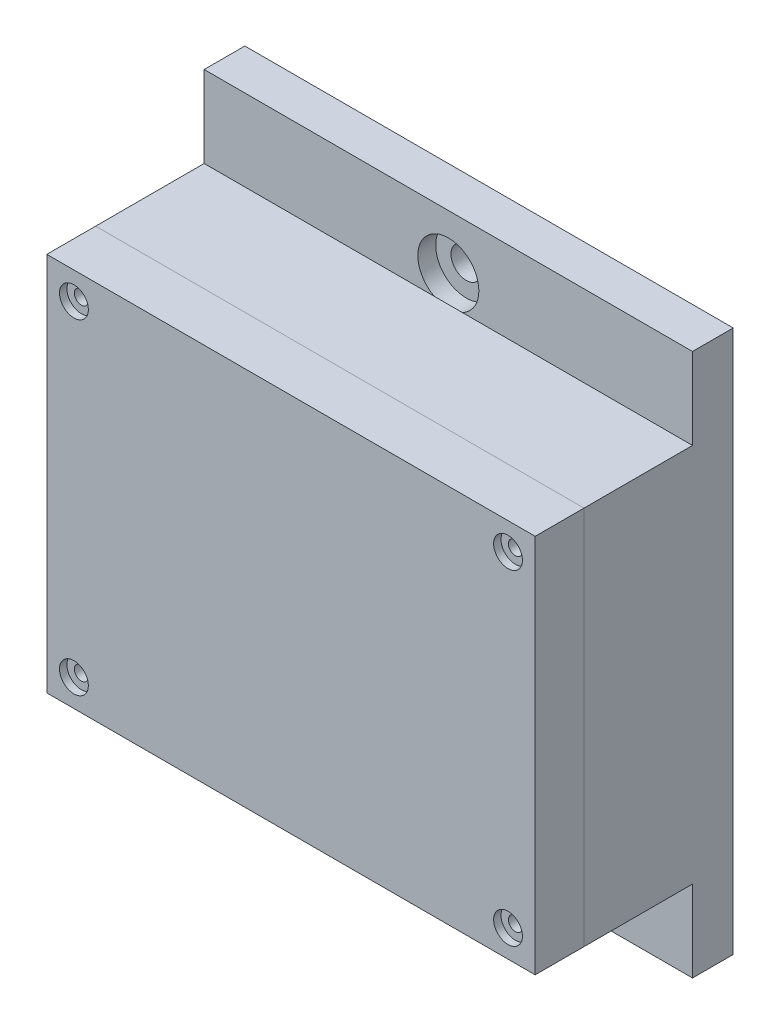
SolidWorks part; units mm, degrees
ref_plane "Front Plane" through (0, 0, 0) normal (0, 0, 1) x (1, 0, 0)
ref_plane "Top Plane" through (0, 0, 0) normal (0, 1, 0) x (1, 0, 0)
ref_plane "Right Plane" through (0, 0, 0) normal (1, 0, 0) x (0, 0, -1)
sketch "Sketch1" plane through (0, 0, 0) normal (0, 0, 1) x (1, 0, 0)
  line L1 (-57.15, 63.5) -> (57.15, 63.5)
  line L2 (-57.15, 63.5) -> (-57.15, -63.5)
  line L3 (-57.15, -63.5) -> (57.15, -63.5)
  line L4 (57.15, 63.5) -> (57.15, -63.5)
  line L5 (-57.15, 63.5) -> (57.15, -63.5) construction
  line L6 (-57.15, -63.5) -> (57.15, 63.5) construction
  point P0 (0, 0)
  dimension "D1" = 127
  dimension "D2" = 114.3
extrude "base" add sketch "Sketch1" along normal blind 9.525
hole_wizard "CBORE for 1/4 Binding Head Machine Screw1" positions "Sketch2" profile "Sketch3" counterbore size "1/4" standard "ANSI Inch" end condition up to next
sketch "Sketch2" plane through (0, 0, 9.525) normal (0, 0, 1) x (1, 0, 0)
  line L12 (-57.15, 63.5) -> (-57.15, -63.5) construction
  line L22 (57.15, -63.5) -> (57.15, 63.5)
  line L23 (57.15, 63.5) -> (-57.15, 63.5)
  line L24 (-57.15, 63.5) -> (-57.15, -63.5)
  line L25 (-57.15, -63.5) -> (57.15, -63.5)
  line L26 (57.15, -63.5) -> (57.15, 63.5)
  line L28 (-57.15, 0) -> (-57.15, -63.5)
  line L29 (-57.15, -63.5) -> (57.15, -63.5)
  line L38 (57.15, 63.5) -> (-57.15, 63.5) construction
  point P2 (0, 50.8)
  point P16 (0, -50.8)
  point P95 (0, 0)
  point P96 (0, 0)
  point P103 (-57.15, -53.0791)
  point P104 (0, 0)
  dimension "D1" = 57.15
  dimension "D2" = 12.7
  dimension "D3" = 12.7
  dimension "D4" = 0
  dimension "D5" = 57.15
sketch "Sketch3" plane through (0, 50.8, 9.525) normal (1, 0, 0) x (0, -1, 0)
  line L0 (0, 0) -> (0, 9.525)
  line L1 (0, 9.525) -> (3.5712, 9.525)
  line L3 (3.5712, 9.525) -> (3.5712, 4.191)
  line L4 (3.5712, 4.191) -> (7.1437, 4.191)
  line L5 (7.1437, 4.191) -> (7.1437, 0)
  line L7 (7.1437, 0) -> (0, 0)
  line L11 (0, -6.35) -> (0, 107.95) construction
  dimension "Thru Hole Dia." = 7.1425
  dimension "Thru Hole Depth" = 9.525
  dimension "C'Bore Dia." = 14.2875
  dimension "C'Bore Depth" = 4.191
sketch "Sketch4" plane through (0, 0, 9.525) normal (0, 0, 1) x (1, 0, 0)
  line L0 (-43.4602, 0) -> (43.4602, 0) construction
  line L1 (-57.15, 44.45) -> (57.15, 44.45)
  line L2 (-57.15, 44.45) -> (-57.15, -44.45)
  line L3 (-57.15, -44.45) -> (57.15, -44.45)
  line L4 (57.15, 44.45) -> (57.15, -44.45)
  line L5 (57.15, 0) -> (43.4602, 0) construction
  line L6 (-43.4602, 0) -> (-57.15, 0) construction
  line L7 (-43.4602, 38.1) -> (43.4602, 38.1)
  line L8 (-43.4602, 38.1) -> (-43.4602, -38.1)
  line L9 (-43.4602, -38.1) -> (43.4602, -38.1)
  line L10 (43.4602, 38.1) -> (43.4602, 18.034)
  line L11 (-43.4602, 38.1) -> (43.4602, -38.1) construction
  line L12 (-43.4602, -38.1) -> (43.4602, 38.1) construction
  line L13 (57.15, 44.45) -> (-57.15, -44.45) construction
  line L14 (3.1115, 38.1) -> (3.1115, 44.45) construction
  line L15 (-35.8402, 30.48) -> (7.3398, 30.48) construction
  line L16 (-35.8402, 30.48) -> (-35.8402, -30.48) construction
  line L17 (-35.8402, -30.48) -> (7.3398, -30.48) construction
  line L18 (7.3398, 30.48) -> (7.3398, -30.48) construction
  line L19 (-35.8402, 30.48) -> (7.3398, -30.48) construction
  line L20 (-35.8402, -30.48) -> (7.3398, 30.48) construction
  line L21 (0, -44.45) -> (0, -38.1) construction
  line L22 (43.4602, -18.034) -> (43.4602, -12.954)
  line L23 (43.4602, 12.954) -> (43.4602, 18.034)
  line L24 (-57.15, 44.45) -> (57.15, -44.45) construction
  line L29 (-57.15, -63.5) -> (57.15, -63.5) construction
  line L30 (-57.15, 63.5) -> (-57.15, -63.5) construction
  line L31 (43.4602, 12.954) -> (43.4602, -12.954)
  line L35 (43.4602, -18.034) -> (43.4602, -38.1)
  line L36 (57.15, 63.5) -> (-57.15, 63.5) construction
  line L37 (43.4602, 0) -> (57.15, 0) construction
  line L38 (57.15, -63.5) -> (57.15, 63.5) construction
  point P5 (-2.4997, -2.1914)
  point P20 (0, 0)
  dimension "D2" = 7.62
  dimension "D3" = 0
  dimension "D4" = 60.96
  dimension "D5" = 43.18
  dimension "D6" = 0
  dimension "D7" = 7.62
  dimension "D8" = 6.35
  dimension "D9" = 13.6898
  dimension "D10" = 21.3098
  dimension "D11" = 33.02
  dimension "D12" = 64.4898
  dimension "D13" = 19.05
  dimension "D14" = 88.9
extrude "Boss-Extrude2" add sketch "Sketch4" along normal blind 25.4
sketch "Sketch11" plane through (0, -44.45, 0) normal (0, -1, 0) x (1, 0, 0)
  line L0 (-37.1102, 34.925) -> (-37.1102, 17.145)
  line L1 (-57.15, 34.925) -> (57.15, 34.925) construction
  line L2 (-37.1102, 17.145) -> (38.3802, 17.145)
  line L3 (38.3802, 17.145) -> (38.3802, 34.925)
  line L4 (38.3802, 34.925) -> (-37.1102, 34.925)
  line L5 (-43.4602, 34.925) -> (-43.4602, 9.525) construction
  dimension "D1" = 17.78
  dimension "D2" = 5.08
  dimension "D3" = 6.35
extrude "Cut-Extrude1" cut sketch "Sketch11" against normal up to next
sketch "Sketch12" plane through (-57.15, 0, 0) normal (-1, 0, 0) x (0, 0, 1)
  line L0 (34.925, 44.45) -> (34.925, -44.45) construction
  line L1 (34.925, 31.75) -> (17.145, 31.75)
  line L2 (34.925, 31.75) -> (34.925, -31.75)
  line L3 (34.925, -31.75) -> (17.145, -31.75)
  line L4 (17.145, 31.75) -> (17.145, -31.75)
  line L5 (34.925, 31.75) -> (17.145, -31.75) construction
  line L6 (34.925, -31.75) -> (17.145, 31.75) construction
  point P0 (26.035, 0)
  dimension "D1" = 6.35
  dimension "D2" = 6.35
  dimension "D3" = 17.78
extrude "Cut-Extrude2" cut sketch "Sketch12" against normal up to next
hole_wizard "#4 Clearance Hole1" positions "Sketch17" profile "Sketch18" hole size "#4" standard "ANSI Inch"
sketch "Sketch17" plane through (0, 0, 34.925) normal (0, 0, 1) x (1, 0, 0)
  line L0 (57.15, -44.45) -> (57.15, 44.45) construction
  line L1 (57.15, 44.45) -> (-57.15, 44.45) construction
  line L3 (38.3802, -44.45) -> (57.15, -44.45) construction
  line L5 (50.8, 38.1) -> (57.15, 38.1) construction
  line L10 (50.8, 38.1) -> (50.8, 44.45) construction
  line L13 (50.8, -38.1) -> (50.8, -44.45) construction
  line L16 (50.8, -38.1) -> (57.15, -38.1) construction
  line L18 (-50.8, 38.1) -> (-57.15, 38.1) construction
  line L19 (-57.15, 44.45) -> (-57.15, 31.75) construction
  line L21 (-50.8, 38.1) -> (-50.8, 44.45) construction
  line L23 (-50.8, -38.1) -> (-50.8, -44.45) construction
  line L24 (-57.15, -44.45) -> (-37.1102, -44.45) construction
  line L26 (-50.8, -38.1) -> (-57.15, -38.1) construction
  line L27 (-57.15, -31.75) -> (-57.15, -44.45) construction
  point P0 (50.8, 38.1)
  point P2 (50.8, -38.1)
  point P4 (-50.8, -38.1)
  point P6 (-50.8, 38.1)
  dimension "D1" = 6.35
sketch "Sketch18" plane through (50.8, 38.1, 34.925) normal (1, 0, 0) x (0, -1, 0)
  line L0 (0, 0) -> (0, 7.3306)
  line L1 (0, 7.3306) -> (1.6319, 6.35)
  line L2 (1.6319, 6.35) -> (1.6319, 0)
  line L5 (1.6319, 0) -> (0, 0)
  line L10 (0, 7.3306) -> (-1.6319, 6.35) construction
  line L11 (0, -6.35) -> (0, 107.95) construction
  dimension "Hole Dia." = 3.2639
  dimension "Hole Depth" = 6.35
  dimension "Drill Angle" = 118
hole_wizard "#4 Clearance Hole2" positions "Sketch21" profile "Sketch20" hole size "#4" standard "ANSI Inch"
sketch "Sketch21" plane through (0, 0, 9.525) normal (0, 0, 1) x (1, 0, 0)
  line L0 (0, 0) -> (-56.3849, 0) construction
  line L2 (-57.15, 31.75) -> (-57.15, -31.75) construction
  line L3 (-57.15, -63.5) -> (57.15, -63.5) construction
  point P0 (-35.814, -30.48)
  point P8 (-35.814, 30.48)
  point P13 (7.366, -30.48)
  point P16 (7.366, 30.48)
  dimension "D1" = 21.336
  dimension "D2" = 33.02
  dimension "D3" = 64.516
sketch "Sketch20" plane through (-35.814, -30.48, 9.525) normal (1, 0, 0) x (0, -1, 0)
  line L0 (0, 0) -> (0, 7.3306)
  line L1 (0, 7.3306) -> (1.6319, 6.35)
  line L2 (1.6319, 6.35) -> (1.6319, 0)
  line L5 (1.6319, 0) -> (0, 0)
  line L10 (0, 7.3306) -> (-1.632, 6.35) construction
  line L11 (0, -6.35) -> (0, 107.95) construction
  dimension "Hole Dia." = 3.2639
  dimension "Hole Depth" = 6.35
  dimension "Drill Angle" = 118
sketch "Sketch23" plane through (0, 0, 9.525) normal (0, 0, 1) x (1, 0, 0)
  line L0 (7.366, 30.48) -> (7.366, -38.1) construction
  line L1 (14.0368, 17.78) -> (20.3868, 17.78)
  line L2 (14.0368, 17.78) -> (14.0368, 5.08)
  line L3 (14.0368, 5.08) -> (20.3868, 5.08)
  line L4 (20.3868, 17.78) -> (20.3868, 5.08)
  line L5 (-43.4602, -38.1) -> (43.4602, -38.1) construction
  line L6 (20.3868, 17.78) -> (14.0368, 5.08) construction
  line L7 (20.3868, 5.08) -> (14.0368, 17.78) construction
  line L8 (-37.1102, -38.1) -> (38.3802, -38.1) construction
  line L9 (28.7485, -38.1) -> (28.7485, 36.8) construction
  line L10 (37.1102, 17.78) -> (43.4602, 5.08) construction
  line L11 (43.4602, 17.78) -> (37.1102, 17.78)
  line L12 (37.1102, 17.78) -> (37.1102, 5.08)
  line L13 (37.1102, 5.08) -> (43.4602, 17.78) construction
  line L14 (43.4602, 5.08) -> (37.1102, 5.08)
  line L15 (43.4602, 17.78) -> (43.4602, 5.08)
  line L16 (43.4602, -38.1) -> (43.4602, 38.1) construction
  point P13 (17.2118, 11.43)
  dimension "D1" = 12.7
  dimension "D2" = 6.35
  dimension "D3" = 0
  dimension "D4" = 43.18
  dimension "D5" = 11.5367
extrude "Boss-Extrude5" add sketch "Sketch23" along normal blind 17.78
hole_wizard "#4 Clearance Hole3" positions "Sketch24" profile "Sketch26" hole size "#4" standard "ANSI Inch"
sketch "Sketch24" plane through (0, 5.08, 0) normal (0, -1, 0) x (-1, 0, 0)
  line L0 (-14.0368, -27.305) -> (-20.3868, -27.305) construction
  line L1 (-37.1102, -27.305) -> (-43.4602, -27.305) construction
  line L2 (-14.0368, -27.305) -> (-14.0368, -9.525) construction
  line L3 (-43.4602, -27.305) -> (-43.4602, -9.525) construction
  point P0 (-17.2118, -20.955)
  point P2 (-40.2852, -20.955)
  dimension "D1" = 6.35
  dimension "D2" = 6.35
  dimension "D3" = 3.175
  dimension "D4" = 3.175
sketch "Sketch26" plane through (17.2118, 5.08, 20.955) normal (1, 0, 0) x (0, 0, -1)
  line L0 (0, 0) -> (0, 7.3306)
  line L1 (0, 7.3306) -> (1.6319, 6.35)
  line L2 (1.6319, 6.35) -> (1.6319, 0)
  line L5 (1.6319, 0) -> (0, 0)
  line L10 (0, 7.3306) -> (-1.632, 6.35) construction
  line L11 (0, -6.35) -> (0, 107.95) construction
  dimension "Hole Dia." = 3.2639
  dimension "Hole Depth" = 6.35
  dimension "Drill Angle" = 118
sketch "Sketch27" plane through (0, 0, 9.525) normal (0, 0, 1) x (1, 0, 0)
  line L0 (-43.4602, -38.1) -> (43.4602, -38.1) construction
  line L1 (14.0368, 5.08) -> (43.4602, 5.08)
  line L2 (14.0368, 5.08) -> (14.0368, -38.1)
  line L3 (14.0368, -38.1) -> (43.4602, -38.1)
  line L4 (43.4602, 5.08) -> (43.4602, -38.1)
  dimension "D1" = 0
  dimension "D2" = 0
extrude "Boss-Extrude6" add sketch "Sketch27" along normal blind 5.08
ref_plane "Plane1" through (0, 0, 40.005) normal (0, 0, 1) x (1, 0, 0)
sketch "Sketch13" plane through (0, 0, 40.005) normal (0, 0, 1) x (1, 0, 0)
  line L0 (-43.4602, 31.75) -> (-57.15, 31.75)
  line L1 (-57.15, 31.75) -> (-57.15, 44.45)
  line L2 (-57.15, 44.45) -> (57.15, 44.45)
  line L3 (57.15, 44.45) -> (57.15, -44.45)
  line L4 (57.15, -44.45) -> (38.3802, -44.45)
  line L5 (38.3802, -44.45) -> (38.3802, -38.1)
  line L6 (38.3802, -38.1) -> (43.4602, -38.1)
  line L7 (43.4602, -38.1) -> (43.4602, 38.1)
  line L8 (43.4602, 38.1) -> (-43.4602, 38.1)
  line L9 (-43.4602, 38.1) -> (-43.4602, 31.75)
  line L10 (-43.4602, -31.75) -> (-57.15, -31.75)
  line L11 (-57.15, -31.75) -> (-57.15, -44.45)
  line L12 (-57.15, -44.45) -> (-37.1102, -44.45)
  line L13 (-37.1102, -44.45) -> (-37.1102, -38.1)
  line L14 (-37.1102, -38.1) -> (-43.4602, -38.1)
  line L15 (-43.4602, -38.1) -> (-43.4602, -31.75)
  line L16 (-57.15, -44.45) -> (-37.1102, -44.45) construction
  line L17 (-37.1102, -38.1) -> (-37.1102, -44.45) construction
  line L18 (-43.4602, -38.1) -> (-37.1102, -38.1) construction
  line L19 (-43.4602, -31.75) -> (-43.4602, -38.1) construction
  line L20 (-43.4602, -31.75) -> (-57.15, -31.75) construction
  line L21 (-57.15, -31.75) -> (-57.15, -44.45) construction
  line L22 (-43.4602, 31.75) -> (-57.15, 31.75) construction
  line L23 (-43.4602, 38.1) -> (-43.4602, 31.75) construction
  line L24 (-57.15, 44.45) -> (-57.15, 31.75) construction
  line L25 (57.15, 44.45) -> (-57.15, 44.45) construction
  line L26 (43.4602, 38.1) -> (-43.4602, 38.1) construction
  line L27 (43.4602, -38.1) -> (43.4602, 38.1) construction
  line L29 (38.3802, -38.1) -> (43.4602, -38.1) construction
  line L30 (38.3802, -44.45) -> (57.15, -44.45) construction
  line L31 (38.3802, -38.1) -> (38.3802, -44.45) construction
  line L32 (57.15, -44.45) -> (57.15, 44.45) construction
extrude "Boss-Extrude3" add sketch "Sketch13" against normal up to surface (5.08 mm away) separate body up to face at (52.4319, 38.1, 34.925)
fillet "Fillet3" radius 2.54 8 edges at (-43.4602, -38.1, 22.225) (43.4602, -38.1, 24.765) (43.4602, 38.1, 22.225) (-43.4602, 38.1, 22.225) (-57.15, 31.75, 26.035) (-57.15, -31.75, 26.035) (38.3802, -44.45, 26.035) (-37.1102, -44.45, 26.035)
sketch "Sketch14" plane through (0, 0, 40.005) normal (0, 0, 1) x (1, 0, 0)
  line L0 (-57.15, 44.45) -> (-57.15, -44.45)
  line L1 (-57.15, -44.45) -> (57.15, -44.45)
  line L2 (57.15, -44.45) -> (57.15, 44.45)
  line L3 (57.15, 44.45) -> (-57.15, 44.45)
extrude "Boss-Extrude4" add sketch "Sketch14" along normal blind 6.35
fillet "Fillet1" radius 2.54 18 edges at (38.3802, -44.45, 37.465) (-57.15, 31.75, 37.465) (-57.15, -31.75, 37.465) (-37.1102, -44.45, 37.465) (38.3802, -41.275, 40.005) (40.9202, -38.1, 40.005) (43.4602, 0, 40.005) (0, 38.1, 40.005) (-43.4602, 34.925, 40.005) (-50.3051, 31.75, 40.005) (-57.15, 0, 40.005) (-50.3051, -31.75, 40.005) (-43.4602, -34.925, 40.005) (-40.2852, -38.1, 40.005) (-37.1102, -41.275, 40.005) (0.635, -44.45, 40.005) (43.4602, 38.1, 37.465) (-43.4602, 38.1, 37.465)
hole_wizard "CBORE for #4 Binding Head Machine Screw1" positions "Sketch28" profile "Sketch29" counterbore size "#4" standard "ANSI Inch"
sketch "Sketch28" plane through (0, 0, 46.355) normal (0, 0, 1) x (1, 0, 0)
  line L0 (57.15, 44.45) -> (-57.15, 44.45) construction
  line L1 (-57.15, 44.45) -> (-57.15, -44.45) construction
  line L2 (-50.8, 38.1) -> (-57.15, 38.1) construction
  line L3 (-57.15, 38.1) -> (-50.8, 38.1) construction
  line L4 (-50.8, 38.1) -> (-50.8, 44.45) construction
  line L6 (-57.15, -44.45) -> (57.15, -44.45) construction
  line L7 (-50.8, -38.1) -> (-50.8, -44.45) construction
  line L8 (-50.8, -44.45) -> (-50.8, -38.1) construction
  line L9 (-50.8, -38.1) -> (-57.15, -38.1) construction
  line L11 (50.8, -38.1) -> (57.15, -38.1) construction
  line L12 (57.15, -44.45) -> (57.15, 44.45) construction
  line L13 (57.15, -38.1) -> (50.8, -38.1) construction
  line L14 (50.8, -38.1) -> (50.8, -44.45) construction
  line L15 (50.8, -44.45) -> (50.8, 38.1) construction
  line L16 (50.8, 38.1) -> (50.8, 44.45) construction
  line L17 (50.8, 44.45) -> (50.8, 38.1) construction
  line L18 (50.8, 38.1) -> (57.15, 38.1) construction
  point P0 (-50.8, -38.1)
  point P2 (-50.8, 38.1)
  point P4 (50.8, 38.1)
  point P6 (50.8, -38.1)
  dimension "D1" = 6.35
  dimension "D2" = 6.35
sketch "Sketch29" plane through (-50.8, -38.1, 46.355) normal (1, 0, 0) x (0, -1, 0)
  line L0 (0, 0) -> (0, 6.0606)
  line L1 (0, 6.0606) -> (1.6319, 5.08)
  line L2 (1.6319, 5.08) -> (1.6319, 1.7272)
  line L3 (1.6319, 1.7272) -> (3.3731, 1.7272)
  line L4 (3.3731, 1.7272) -> (3.3731, 0)
  line L5 (3.3731, 0) -> (0, 0)
  line L10 (0, 6.0606) -> (-1.632, 5.08) construction
  line L11 (0, -6.35) -> (0, 107.95) construction
  dimension "Hole Dia." = 3.2639
  dimension "Hole Depth" = 5.08
  dimension "C'Bore Dia." = 6.7462
  dimension "C'Bore Depth" = 1.7272
  dimension "Drill Angle" = 118
